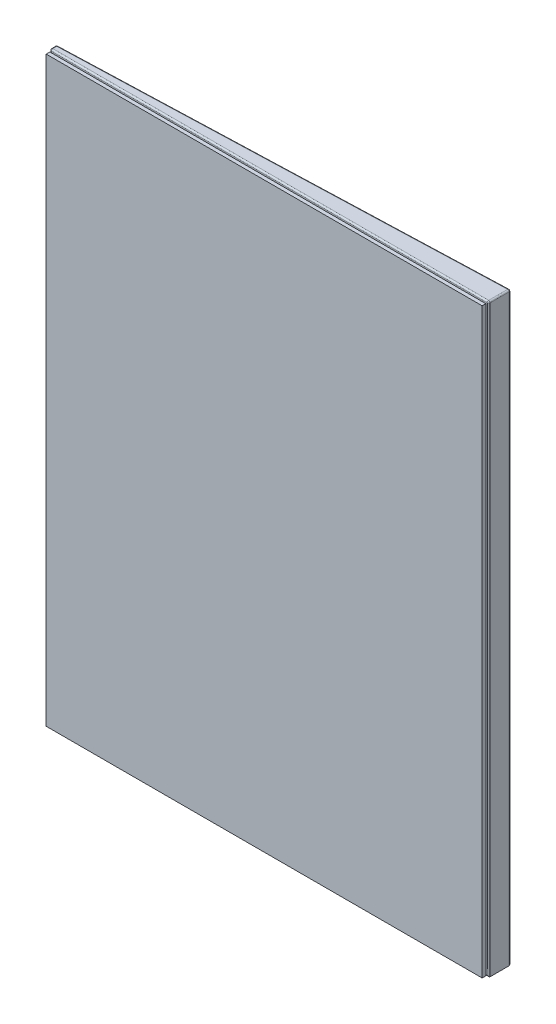
SolidWorks part; units mm, degrees
ref_plane "Front Plane" through (0, 0, 0) normal (0, 0, 1) x (1, 0, 0)
ref_plane "Top Plane" through (0, 0, 0) normal (0, 1, 0) x (1, 0, 0)
ref_plane "Right Plane" through (0, 0, 0) normal (1, 0, 0) x (0, 0, -1)
sketch "Sketch1" plane through (0, 0, 0) normal (0, 1, 0) x (1, 0, 0)
  line L0 (0, 0) -> (76.2, 0)
  line L1 (76.2, 0) -> (76.2, 3.81)
  line L2 (76.2, 3.81) -> (0, 1.1764)
  line L3 (0, 1.1764) -> (0, 0)
  dimension "D1" = 3.81
  dimension "D2" = 1.1764
  dimension "D3" = 76.2
extrude "Boss-Extrude1" add sketch "Sketch1" along normal blind 101.6
fillet "Fillet1" radius 0.254 11 edges at (38.1, 0, -2.4932) (76.2, 50.8, -3.81) (38.1, 0, 0) (0, 0, -0.5882) (0, 50.8, -1.1764) (0, 50.8, 0) (76.2, 50.8, 0) (76.2, 101.6, -1.905) (0, 101.6, -0.5882) (38.1, 101.6, 0) (38.1, 101.6, -2.4932)
sketch "Sketch3" plane through (0, 0, 0) normal (0, 0, 1) x (1, 0, 0)
  line L14 (1.524, 1.524) -> (74.676, 1.524)
  line L15 (74.676, 1.524) -> (74.676, 100.076)
  line L16 (74.676, 100.076) -> (1.524, 100.076)
  line L17 (1.524, 100.076) -> (1.524, 1.524)
  line L18 (1.524, 1.524) -> (74.676, 1.524)
  line L19 (74.676, 1.524) -> (74.676, 100.076)
  line L20 (74.676, 100.076) -> (1.524, 100.076)
  line L21 (1.524, 100.076) -> (1.524, 1.524)
  dimension "D1" = 1.27
extrude "Boss-Extrude2" add sketch "Sketch3" along normal blind 0.254
sketch "Sketch4" plane through (0, 0, 0.254) normal (0, 0, 1) x (1, 0, 0)
  line L0 (0.254, 0.254) -> (75.946, 0.254) construction
  line L1 (75.946, 0.254) -> (75.946, 101.346) construction
  line L2 (75.946, 101.346) -> (0.254, 101.346) construction
  line L3 (0.254, 101.346) -> (0.254, 0.254) construction
  line L4 (0.254, 0.254) -> (75.946, 0.254)
  line L5 (75.946, 0.254) -> (75.946, 101.346)
  line L6 (75.946, 101.346) -> (0.254, 101.346)
  line L7 (0.254, 101.346) -> (0.254, 0.254)
extrude "Boss-Extrude3" add sketch "Sketch4" along normal blind 0.635
sketch "Sketch5" plane through (-0.0406, 0, -1.175) normal (-0.0345, 0, -0.9994) x (-0.9994, 0, 0.0345)
  line L0 (-6.4973, 100.5576) -> (-1.2517, 100.5576)
  line L1 (-74.1755, 99.8594) -> (-68.9299, 99.8594)
  line L2 (-74.1755, 99.8594) -> (-74.1755, 91.3353)
  line L3 (-74.1755, 91.3353) -> (-68.9299, 91.3353)
  line L4 (-68.9299, 99.8594) -> (-68.9299, 91.3353)
  line L5 (-6.4973, 100.5576) -> (-6.4973, 92.0336)
  line L6 (-6.4973, 92.0336) -> (-1.2517, 92.0336)
  line L7 (-1.2517, 100.5576) -> (-1.2517, 92.0336)
  line L8 (-74.3584, 10.0636) -> (-69.1128, 10.0636)
  line L9 (-74.3584, 10.0636) -> (-74.3584, 1.5395)
  line L10 (-74.3584, 1.5395) -> (-69.1128, 1.5395)
  line L11 (-69.1128, 10.0636) -> (-69.1128, 1.5395)
  line L12 (-7.0463, 10.0385) -> (-1.8007, 10.0385)
  line L13 (-7.0463, 10.0385) -> (-7.0463, 1.5145)
  line L14 (-7.0463, 1.5145) -> (-1.8007, 1.5145)
  line L15 (-1.8007, 10.0385) -> (-1.8007, 1.5145)
  dimension "D1" = 8.5241
  dimension "D2" = 5.2456
extrude "Boss-Extrude4" add sketch "Sketch5" along normal blind 0.635
